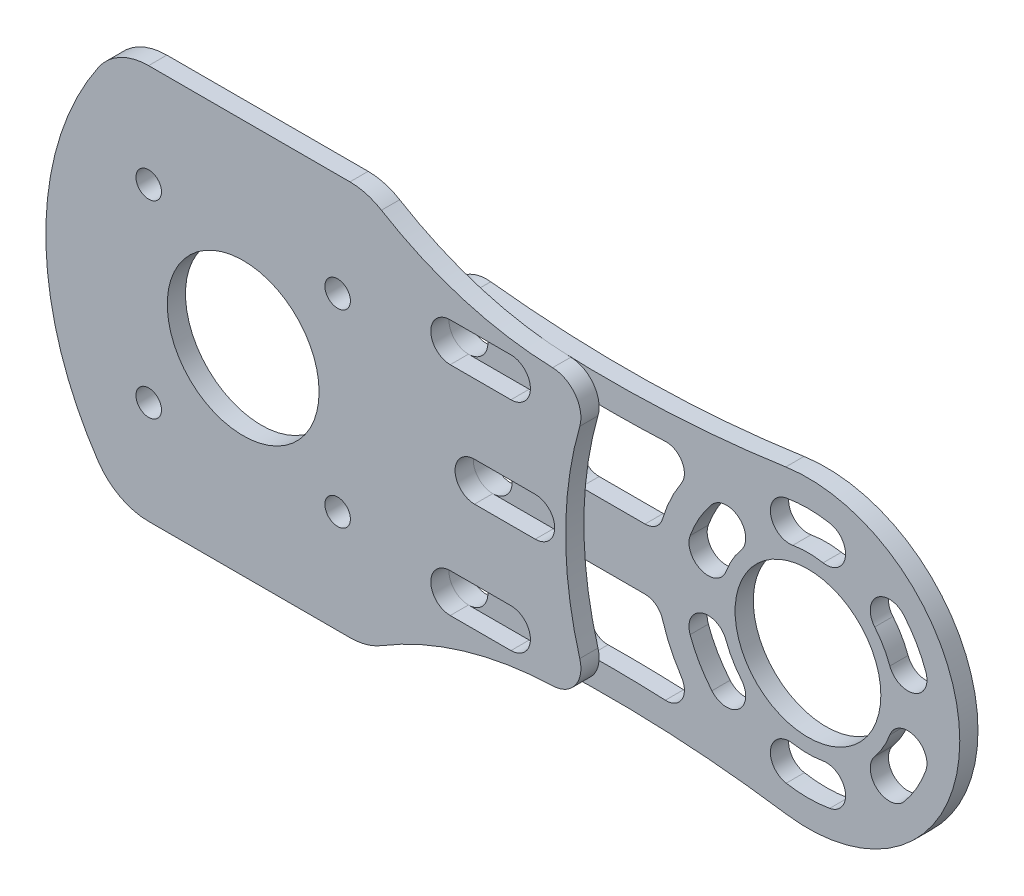
SolidWorks part; units mm, degrees
ref_plane "정면" through (0, 0, 0) normal (0, 0, 1) x (1, 0, 0)
ref_plane "윗면" through (0, 0, 0) normal (0, 1, 0) x (1, 0, 0)
ref_plane "우측면" through (0, 0, 0) normal (1, 0, 0) x (0, 0, -1)
sketch "스케치2" plane through (0, 0, 0) normal (0, 0, 1) x (1, 0, 0)
  line L0 (-90, 0) -> (-100, 0) construction
  circle A0 centre (0, 0) radius 25
  circle A2 centre (-100, 0) radius 32.5 construction
  arc A3 (-90.6126, 31.1147) -> (-3.6493, 24.7322) centre (-32.8437, 222.59) ccw
  arc A4 (-90.6126, -31.1147) -> (-3.6493, -24.7322) centre (-32.8437, -222.59) cw
  circle A6 centre (-90, 0) radius 32.5
  dimension "D1" = 50
  dimension "D2" = 100
  dimension "D4" = 65
  dimension "D5" = 200
  dimension "D7" = 10
extrude "Truck" add sketch "스케치2" along normal blind 3 contours A0 | A6 A4 A0 A3
sketch "스케치1" plane through (0, 0, 0) normal (0, 0, 1) x (1, 0, 0)
  circle A1 centre (0, 0) radius 12
  dimension "D1" = 24
extrude "컷-돌출1" cut sketch "스케치1" along normal through all
sketch "스케치3" plane through (0, 0, 0) normal (0, 0, 1) x (1, 0, 0)
  line L0 (0, 0) -> (0, 17.5) construction
  line L1 (0, 0) -> (-3.0388, 17.2341) construction
  line L2 (0, 0) -> (3.0388, 17.2341) construction
  circle A0 centre (0, 0) radius 17.5 construction
  arc A1 (3.0388, 17.2341) -> (-3.0388, 17.2341) centre (0, 0) ccw construction
  arc A2 (3.5858, 20.3363) -> (-3.5858, 20.3363) centre (0, 0) ccw
  arc A3 (2.4919, 14.132) -> (-2.4919, 14.132) centre (0, 0) ccw
  arc A4 (2.4919, 14.132) -> (3.5858, 20.3363) centre (3.0388, 17.2341) ccw
  arc A5 (-3.5858, 20.3363) -> (-2.4919, 14.132) centre (-3.0388, 17.2341) ccw
  point P5 (0, 17.5)
  dimension "D1" = 35
  dimension "D2" = 3.15
  dimension "D3" = 20
extrude "컷-돌출2" cut sketch "스케치3" along normal through all
pattern_circular "원형 패턴1" count 6 over 360 about axis through (0, 0, 0) along (0, 0, 1) of "컷-돌출2"
fillet "필렛1" radius 6 2 edges at (-70.8044, -26.2255, 1.5) (-70.8044, 26.2255, 1.5)
hole_wizard "M6 여유 구멍1" positions "스케치9" profile "스케치10" hole size "M6" standard "Ansi Metric" end condition up to next
sketch "스케치9" plane through (0, 0, 0) normal (0, 0, -1) x (-1, 0, 0)
  arc A6 (61.2197, 15.0977) -> (55.2346, 23.8473) centre (55.9064, 17.885) ccw construction
  arc A7 (55.2346, -23.8473) -> (61.2197, -15.0977) centre (55.9064, -17.885) ccw construction
  point P0 (55.9064, 17.885)
  point P3 (55.9064, -17.885)
  point P8 (51.9064, 0)
  dimension "D1" = 4
sketch "스케치10" plane through (-55.9064, 17.885, 0) normal (1, 0, 0) x (0, 1, 0)
  line L0 (0, 0) -> (0, 3)
  line L1 (0, 3) -> (3.2, 3)
  line L2 (3.2, 3) -> (3.2, 0)
  line L5 (3.2, 0) -> (0, 0)
  line L11 (0, -6.35) -> (0, 107.95) construction
  dimension "관통 구멍 지름" = 6.4
  dimension "관통 구멍 깊이" = 3
sketch "스케치4" plane through (0, 0, 3) normal (0, 0, 1) x (1, 0, 0)
  line L0 (-51.9064, 0) -> (-41.9064, 0) construction
  line L1 (-90, 0) -> (-100, 0) construction
  line L2 (-122.5, 0) -> (-57.5, 0) construction
  line L4 (-110.4967, 32.5) -> (-69.5033, 32.5)
  line L5 (-110.4967, -32.5) -> (-69.5033, -32.5)
  line L6 (-90, 32.5) -> (-90, -32.5) construction
  circle A0 centre (-90, 0) radius 32.5 construction
  arc A3 (-39.0439, 22.6861) -> (-69.5033, 32.5) centre (-37.2533, 80.4188) cw
  arc A4 (-39.0439, -22.6861) -> (-69.5033, -32.5) centre (-37.2533, -80.4188) ccw
  arc A6 (-110.4967, 32.5) -> (-110.4967, -32.5) centre (-72.5, 0) ccw
  arc A7 (-69.5033, -32.5) -> (-69.5033, 32.5) centre (-107.5, 0) ccw construction
  arc A8 (-34.576, -16.5593) -> (-39.0439, -22.6861) centre (-39.1928, -17.885) cw
  arc A10 (-34.576, 16.5593) -> (-39.0439, 22.6861) centre (-39.1928, 17.885) ccw
  arc A11 (-34.576, 16.5593) -> (-34.576, -16.5593) centre (23.0936, 0) ccw
  arc A12 (-90.6126, 31.1147) -> (-3.6493, 24.7322) centre (-32.8437, 222.59) ccw construction
  point P29 (-90, 0)
  point P42 (-36.9064, 0)
  dimension "D1" = 60
  dimension "D2" = 50
  dimension "D5" = 5
extrude "Motor" add sketch "스케치4" along normal blind 3 separate body
sketch "스케치5" plane through (0, 0, 3) normal (0, 0, 1) x (1, 0, 0)
  line L0 (-122.5, 0) -> (-57.5, 0) construction
  circle A0 centre (-90, 0) radius 12.5
  dimension "D1" = 25
extrude "컷-돌출3" cut sketch "스케치5" along normal up to body (3 mm away)
hole_wizard "M4 여유 구멍1" positions "스케치6" profile "스케치7" hole size "M4" standard "Ansi Metric"
sketch "스케치6" plane through (0, 0, 3) normal (0, 0, 1) x (1, 0, 0)
  circle A1 centre (-90, 0) radius 22 construction
  point P0 (-74.4437, 15.5563)
  point P22 (-74.4437, -15.5563)
  point P23 (-105.5563, -15.5563)
  point P24 (-105.5563, 15.5563)
  point P25 (-90, 0)
  dimension "D1" = 44
  dimension "D2" = 4
sketch "스케치7" plane through (-74.4437, 15.5563, 3) normal (1, 0, 0) x (0, 1, 0)
  line L0 (0, 0) -> (0, 3)
  line L1 (0, 3) -> (2.1, 3)
  line L2 (2.1, 3) -> (2.1, 0)
  line L5 (2.1, 0) -> (0, 0)
  line L11 (0, -6.35) -> (0, 107.95) construction
  dimension "관통 구멍 지름" = 4.2
  dimension "관통 구멍 깊이" = 3
sketch "스케치13" plane through (0, 0, 3) normal (0, 0, 1) x (1, 0, 0)
  line L0 (-45.9064, 17.885) -> (-55.9064, 17.885) construction
  line L1 (-45.9064, 14.685) -> (-55.9064, 14.685)
  line L2 (-45.9064, 21.085) -> (-55.9064, 21.085)
  line L3 (-45.9064, -17.885) -> (-55.9064, -17.885) construction
  line L4 (-45.9064, -21.085) -> (-55.9064, -21.085)
  line L5 (-45.9064, -14.685) -> (-55.9064, -14.685)
  line L6 (-41.9064, 0) -> (-51.9064, 0) construction
  line L7 (-41.9064, -3.2) -> (-51.9064, -3.2)
  line L8 (-41.9064, 3.2) -> (-51.9064, 3.2)
  line L9 (-51.9064, 0) -> (-41.9064, 0) construction
  arc A0 (-45.9064, 14.685) -> (-45.9064, 21.085) centre (-45.9064, 17.885) ccw
  arc A1 (-55.9064, 21.085) -> (-55.9064, 14.685) centre (-55.9064, 17.885) ccw
  arc A2 (-45.9064, -21.085) -> (-45.9064, -14.685) centre (-45.9064, -17.885) ccw
  arc A3 (-55.9064, -14.685) -> (-55.9064, -21.085) centre (-55.9064, -17.885) ccw
  arc A4 (-41.9064, -3.2) -> (-41.9064, 3.2) centre (-41.9064, 0) ccw
  arc A5 (-51.9064, 3.2) -> (-51.9064, -3.2) centre (-51.9064, 0) ccw
  point P4 (-50.9064, 17.885)
  point P9 (-50.9064, -17.885)
  point P20 (-46.9064, 0)
  dimension "D1" = 3.2
extrude "컷-돌출4" cut sketch "스케치13" along normal up to body (3 mm away)
sketch "스케치14" plane through (0, 0, 3) normal (0, 0, 1) x (1, 0, 0)
  line L0 (0, 25) -> (0, 20.65) construction
  line L1 (0, 0) -> (-40.9064, 0) construction
  line L2 (-24.4949, 5) -> (-40.7107, 5)
  line L3 (-24.4949, -5) -> (-40.7107, -5)
  line L4 (-27.4289, 18.3117) -> (-27.5442, 22.6602) construction
  line L5 (-27.4289, -18.3117) -> (-27.5442, -22.6602) construction
  arc A0 (-16.3573, 18.9061) -> (-16.3573, -18.9061) centre (0, 0) ccw
  arc A1 (-3.6493, -24.7322) -> (-3.6493, 24.7322) centre (0, 0) ccw construction
  arc A2 (-55.2346, 23.8473) -> (-3.6493, 24.7322) centre (-32.8437, 222.59) ccw construction
  arc A3 (-3.6493, -24.7322) -> (-55.2346, -23.8473) centre (-32.8437, -222.59) ccw construction
  arc A4 (3.5858, 20.3363) -> (-3.5858, 20.3363) centre (0, 0) ccw construction
  arc A8 (-39.1679, -18.688) -> (-38.4207, -17.6633) centre (-39.1928, -17.885) ccw
  arc A9 (-39.1679, -18.688) -> (-38.4207, -17.6633) centre (-39.1928, -17.885) ccw
  arc A10 (-38.4207, 17.6633) -> (-39.1679, 18.688) centre (-39.1928, 17.885) ccw
  arc A11 (-38.4207, 17.6633) -> (-39.1679, 18.688) centre (-39.1928, 17.885) ccw
  arc A15 (-38.4207, 17.6633) -> (-38.4207, -17.6633) centre (23.0936, 0) ccw
  arc A17 (-38.5166, 18.3187) -> (-16.3573, 18.9061) centre (-32.8437, 222.59) ccw
  arc A20 (-16.3573, -18.9061) -> (-38.5166, -18.3187) centre (-32.8437, -222.59) ccw
  arc A21 (-38.4207, 17.6633) -> (-38.4207, -17.6633) centre (23.0936, 0) ccw
  dimension "D3" = 10
  dimension "D1" = 4
extrude "컷-돌출5" cut sketch "스케치14" against normal up to body (3 mm away)
fillet "필렛3" radius 3 8 edges at (-24.4949, -5, 1.5) (-16.3573, -18.9061, 1.5) (-24.4949, 5, 1.5) (-16.3573, 18.9061, 1.5) (-40.7107, 5, 1.5) (-38.5166, -18.3187, 1.5) (-40.7107, -5, 1.5) (-38.5166, 18.3187, 1.5)
fillet "필렛4" radius 10 4 edges at (-110.4967, -32.5, 4.5) (-69.5033, -32.5, 4.5) (-69.5033, 32.5, 4.5) (-110.4967, 32.5, 4.5)
delete or keep bodies "바디-삭제/보존 1" [suppressed] type delete bodies bodies 112
delete or keep bodies "바디-삭제/보존 2" [suppressed] type delete bodies bodies 110
sketch "스케치15" [suppressed] plane through (0, 0, 0) normal (0, 0, 1) x (1, 0, 0)
  line L0 (0, 0) -> (-122.5, 0) construction
  line L1 (-88.9974, 32.5) -> (-88.9974, -32.5) construction
  line L2 (-105.5719, 32.5) -> (-72.4228, 32.5) construction
  line L3 (-105.5719, -32.5) -> (-72.4228, -32.5) construction
  line L4 (-110.249, 31.3388) -> (-105.5719, 22.5) construction
  circle A0 centre (-109.0114, 29) radius 2
  arc A1 (-113.8399, 28.125) -> (-113.8399, -28.125) centre (-72.5, 0) ccw construction
  circle A2 centre (-109.0114, -29) radius 2
  circle A3 centre (-68.9833, -29) radius 2
  circle A4 centre (-68.9833, 29) radius 2
  arc A5 (-105.5719, 32.5) -> (-113.8399, 28.125) centre (-105.5719, 22.5) ccw construction
  dimension "D1" = 4
  dimension "D2" = 29
extrude "컷-돌출7" [suppressed] cut sketch "스케치15" along normal through all
